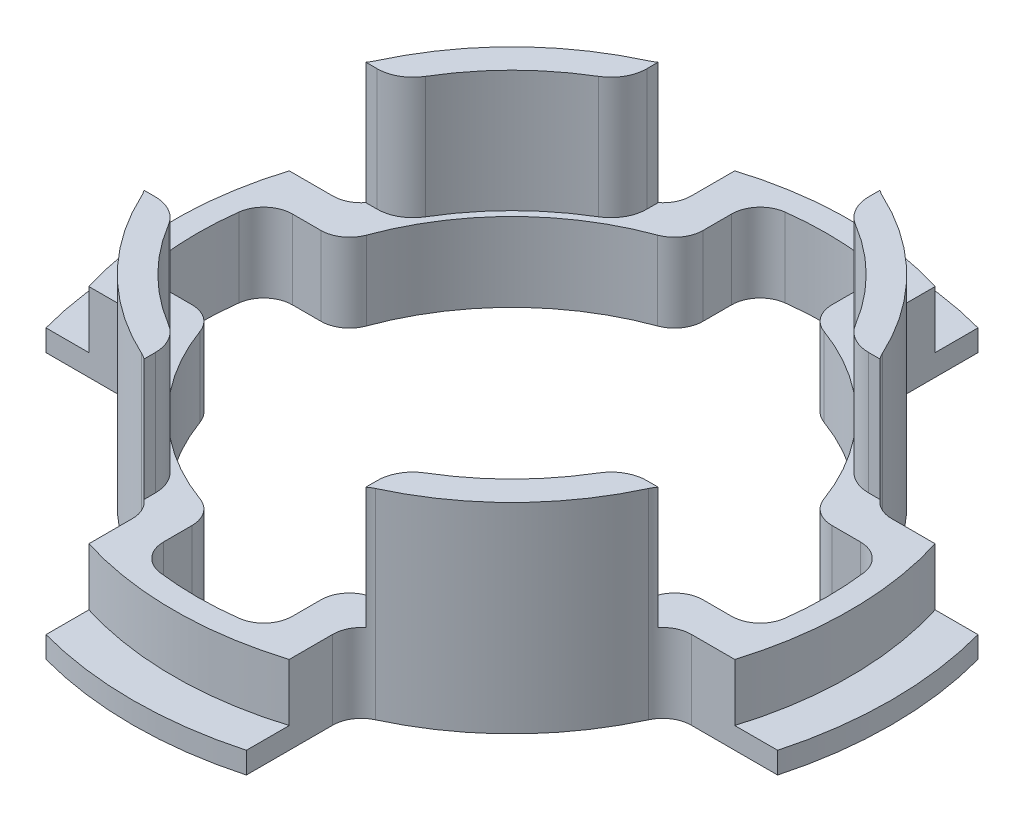
SolidWorks part; units mm, degrees
ref_plane "前视基准面" through (0, 0, 0) normal (0, 0, 1) x (1, 0, 0)
ref_plane "上视基准面" through (0, 0, 0) normal (0, 1, 0) x (1, 0, 0)
ref_plane "右视基准面" through (0, 0, 0) normal (1, 0, 0) x (0, 0, -1)
sketch "草图1" plane through (0, -4.8977, 0) normal (0, -1, 0) x (1, 0, 0)
  line L0 (1.4, 4.3818) -> (1.4, 3.6401)
  line L1 (4.3818, 1.4) -> (3.6401, 1.4)
  line L2 (4.3818, -1.4) -> (3.6401, -1.4)
  line L3 (1.4, -4.3818) -> (1.4, -3.6401)
  line L4 (-1.4, -4.3818) -> (-1.4, -3.6401)
  line L5 (-4.3818, -1.4) -> (-3.6401, -1.4)
  line L6 (-4.3818, 1.4) -> (-3.6401, 1.4)
  line L7 (-1.4, 4.3818) -> (-1.4, 3.6401)
  line L8 (0, 0) -> (0, 2.522) construction
  line L9 (1.75, 2.522) -> (-1.75, 2.522) construction
  arc A0 (1.4, 4.3818) -> (-1.4, 4.3818) centre (0, 0) ccw
  circle A1 centre (0, 0) radius 3.4
  arc A3 (1.4, 3.6401) -> (3.6401, 1.4) centre (0, 0) cw
  arc A4 (3.6401, -1.4) -> (1.4, -3.6401) centre (0, 0) cw
  arc A5 (-1.4, -3.6401) -> (-3.6401, -1.4) centre (0, 0) cw
  arc A6 (-3.6401, 1.4) -> (-1.4, 3.6401) centre (0, 0) cw
  arc A7 (-4.3818, 1.4) -> (-4.3818, -1.4) centre (0, 0) ccw
  arc A8 (-1.4, -4.3818) -> (1.4, -4.3818) centre (0, 0) ccw
  arc A9 (4.3818, -1.4) -> (4.3818, 1.4) centre (0, 0) ccw
  dimension "D1" = 6.8
  dimension "D2" = 4
  dimension "D4" = 3.9
  dimension "D5" = 4.6
  dimension "D3" = 2.8
extrude "凸台-拉伸1" add sketch "草图1" against normal blind 1.1
sketch "草图2" plane through (0, -4.16, 0) normal (0, -1, 0) x (1, 0, 0)
  line L0 (4.2767, 1.4) -> (4.5128, 1.4)
  line L1 (0, 0) -> (6.2123, 0) construction
  line L2 (4.2767, -1.4) -> (4.5128, -1.4)
  line L3 (1.4, -4.2767) -> (1.4, -4.5128)
  line L4 (-1.4, -4.2767) -> (-1.4, -4.5128)
  line L5 (-4.2767, -1.4) -> (-4.5128, -1.4)
  line L6 (-4.2767, 1.4) -> (-4.5128, 1.4)
  line L7 (-1.4, 4.2767) -> (-1.4, 4.5128)
  line L8 (1.4, 4.2767) -> (1.4, 4.5128)
  line L9 (3.6401, -1.4) -> (4.3818, -1.4) construction
  arc A0 (1.4, 4.5128) -> (-1.4, 4.5128) centre (0, 0) ccw
  arc A1 (1.4, 4.2767) -> (-1.4, 4.2767) centre (0, 0) ccw
  arc A2 (4.2767, -1.4) -> (4.2767, 1.4) centre (0, 0) ccw
  arc A3 (4.5128, -1.4) -> (4.5128, 1.4) centre (0, 0) ccw
  arc A4 (-1.4, -4.2767) -> (1.4, -4.2767) centre (0, 0) ccw
  arc A5 (-1.4, -4.5128) -> (1.4, -4.5128) centre (0, 0) ccw
  arc A6 (-4.2767, 1.4) -> (-4.2767, -1.4) centre (0, 0) ccw
  arc A7 (-4.5128, 1.4) -> (-4.5128, -1.4) centre (0, 0) ccw
  dimension "D1" = 9.45
  dimension "D2" = 4.5
  dimension "D4" = 4
extrude "凸台-拉伸2" add sketch "草图2" along normal up to surface (1.1 mm away) from surface
sketch "草图3" plane through (0, -3.7977, 0) normal (0, 1, 0) x (-1, 0, 0)
  line L0 (-3.6401, -1.4) -> (-4.5128, -1.4) construction
  line L4 (4.2767, 1.4) -> (5.1118, 1.4)
  line L5 (4.2767, -1.4) -> (5.1118, -1.4)
  line L6 (-1.4, -4.2767) -> (-1.4, -5.1118)
  line L7 (1.4, -4.2767) -> (1.4, -5.1118)
  line L8 (-4.2767, 1.4) -> (-5.1118, 1.4)
  line L9 (-4.2767, -1.4) -> (-5.1118, -1.4)
  line L10 (1.4, 4.2767) -> (1.4, 5.1118)
  line L11 (-1.4, 4.2767) -> (-1.4, 5.1118)
  arc A0 (4.2767, 1.4) -> (4.2767, -1.4) centre (0, 0) cw
  arc A2 (5.1118, -1.4) -> (5.1118, 1.4) centre (0, 0) ccw
  arc A3 (1.4, -4.2767) -> (-1.4, -4.2767) centre (0, 0) cw
  arc A4 (-1.4, -5.1118) -> (1.4, -5.1118) centre (0, 0) ccw
  arc A5 (-4.2767, -1.4) -> (-4.2767, 1.4) centre (0, 0) cw
  arc A6 (-5.1118, 1.4) -> (-5.1118, -1.4) centre (0, 0) ccw
  arc A7 (-1.4, 4.2767) -> (1.4, 4.2767) centre (0, 0) cw
  arc A8 (1.4, 5.1118) -> (-1.4, 5.1118) centre (0, 0) ccw
  dimension "D1" = 5.3
  dimension "D3" = 4.5
  dimension "D2" = 4
extrude "凸台-拉伸3" add sketch "草图3" along normal blind 0.3 from surface at -1.1 starting at face at (0, -4.8977, 0)
fillet "圆角1" [suppressed] radius 1
sketch "草图4" plane through (0, -4.8977, 0) normal (0, 1, 0) x (-1, 0, 0)
  line L2 (1.55, 3.5788) -> (1.55, 3.1381)
  line L3 (3.1381, 1.55) -> (3.5788, 1.55)
  line L4 (1.55, -3.1381) -> (1.55, -3.5788)
  line L5 (3.5788, -1.55) -> (3.1381, -1.55)
  line L6 (-3.1381, -1.55) -> (-3.5788, -1.55)
  line L7 (-1.55, -3.5788) -> (-1.55, -3.1381)
  line L8 (-1.55, 3.1381) -> (-1.55, 3.5788)
  line L9 (-3.5788, 1.55) -> (-3.1381, 1.55)
  arc A0 (1.55, 3.5788) -> (3.5788, 1.55) centre (0, 0) cw
  arc A2 (1.55, 3.1381) -> (3.1381, 1.55) centre (0, 0) cw
  arc A3 (3.5788, -1.55) -> (1.55, -3.5788) centre (0, 0) cw
  arc A4 (3.1381, -1.55) -> (1.55, -3.1381) centre (0, 0) cw
  arc A5 (-1.55, -3.5788) -> (-3.5788, -1.55) centre (0, 0) cw
  arc A6 (-1.55, -3.1381) -> (-3.1381, -1.55) centre (0, 0) cw
  arc A7 (-3.5788, 1.55) -> (-1.55, 3.5788) centre (0, 0) cw
  arc A8 (-3.1381, 1.55) -> (-1.55, 3.1381) centre (0, 0) cw
  arc A9 (-1.4, 3.6401) -> (-3.6401, 1.4) centre (0, 0) ccw construction
  dimension "D2" = 3.5
  dimension "D3" = 3.1
  dimension "D1" = 4
extrude "凸台-拉伸4" add sketch "草图4" along normal blind 1.7 from surface at 1.1 starting at face at (0, -3.7977, 0)
fillet "圆角2" radius 0.5 8 edges at (3.1381, -2.9477, -1.55) (1.55, -2.9477, -3.1381) (1.55, -2.9477, 3.1381) (3.1381, -2.9477, 1.55) (-1.55, -2.9477, 3.1381) (-3.1381, -2.9477, 1.55) (-3.1381, -2.9477, -1.55) (-1.55, -2.9477, -3.1381)
fillet "圆角3" radius 0.4 8 edges at (-3.6401, -4.3477, 1.4) (-3.6401, -4.3477, -1.4) (-1.4, -4.3477, -3.6401) (1.4, -4.3477, -3.6401) (3.6401, -4.3477, -1.4) (3.6401, -4.3477, 1.4) (1.4, -4.3477, 3.6401) (-1.4, -4.3477, 3.6401)
fillet "圆角4" [suppressed] radius 0.1
sketch "草图5" plane through (0, -3.7977, 0) normal (0, 1, 0) x (-1, 0, 0)
  line L0 (4.307, 0.9) -> (2.74, 0.9)
  line L1 (2.74, 0.9) -> (2.74, -0.9)
  line L2 (2.74, -0.9) -> (4.307, -0.9)
  line L3 (0, 0) -> (2.0968, 0) construction
  line L4 (0.9, -4.307) -> (0.9, -2.74)
  line L5 (0.9, -2.74) -> (-0.9, -2.74)
  line L6 (-0.9, -2.74) -> (-0.9, -4.307)
  line L7 (-4.307, -0.9) -> (-2.74, -0.9)
  line L8 (-2.74, -0.9) -> (-2.74, 0.9)
  line L9 (-2.74, 0.9) -> (-4.307, 0.9)
  line L10 (-0.9, 4.307) -> (-0.9, 2.74)
  line L11 (-0.9, 2.74) -> (0.9, 2.74)
  line L12 (0.9, 2.74) -> (0.9, 4.307)
  arc A4 (4.307, 0.9) -> (4.307, -0.9) centre (0, 0) cw
  arc A6 (0.9, -4.307) -> (-0.9, -4.307) centre (0, 0) cw
  arc A7 (-4.307, -0.9) -> (-4.307, 0.9) centre (0, 0) cw
  arc A8 (-0.9, 4.307) -> (0.9, 4.307) centre (0, 0) cw
  dimension "D2" = 0.9
  dimension "D3" = 4
  dimension "D1" = 0.9
  dimension "D4" = 4.4
extrude "切除-拉伸1" cut sketch "草图5" against normal through all
fillet "圆角5" radius 0.4 16 edges at (-0.9, -4.3477, 4.307) (0.9, -4.3477, 4.307) (4.307, -4.3477, 0.9) (4.307, -4.3477, -0.9) (0.9, -4.3477, -4.307) (-0.9, -4.3477, -4.307) (-4.307, -4.3477, 0.9) (-4.307, -4.3477, -0.9) (-3.2787, -4.3477, -0.9) (3.2787, -4.3477, 0.9) (3.2787, -4.3477, -0.9) (0.9, -4.3477, 3.2787) (-0.9, -4.3477, 3.2787) (-3.2787, -4.3477, 0.9) (0.9, -4.3477, -3.2787) (-0.9, -4.3477, -3.2787)
fillet "圆角6" [suppressed] radius 0.4
chamfer "倒角1" [suppressed] distance 0.2 angle 45
